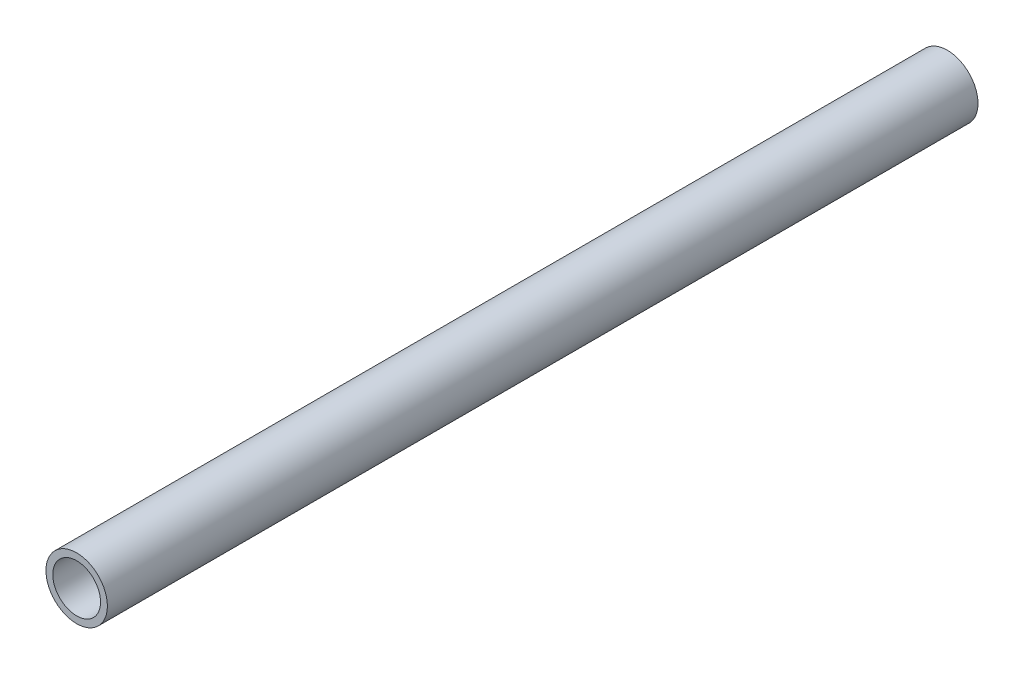
SolidWorks part; units mm, degrees
ref_plane "Front Plane" through (0, 0, 0) normal (0, 0, 1) x (1, 0, 0)
ref_plane "Top Plane" through (0, 0, 0) normal (0, 1, 0) x (1, 0, 0)
ref_plane "Right Plane" through (0, 0, 0) normal (1, 0, 0) x (0, 0, -1)
sketch "Sketch1" plane through (0, 0, 0) normal (0, 0, 1) x (1, 0, 0)
  circle A0 centre (0, 0) radius 7
  circle A1 centre (0, 0) radius 9
  dimension "D1" = 14
  dimension "D2" = 18
extrude "Boss-Extrude1" add sketch "Sketch1" along normal blind 255.08
